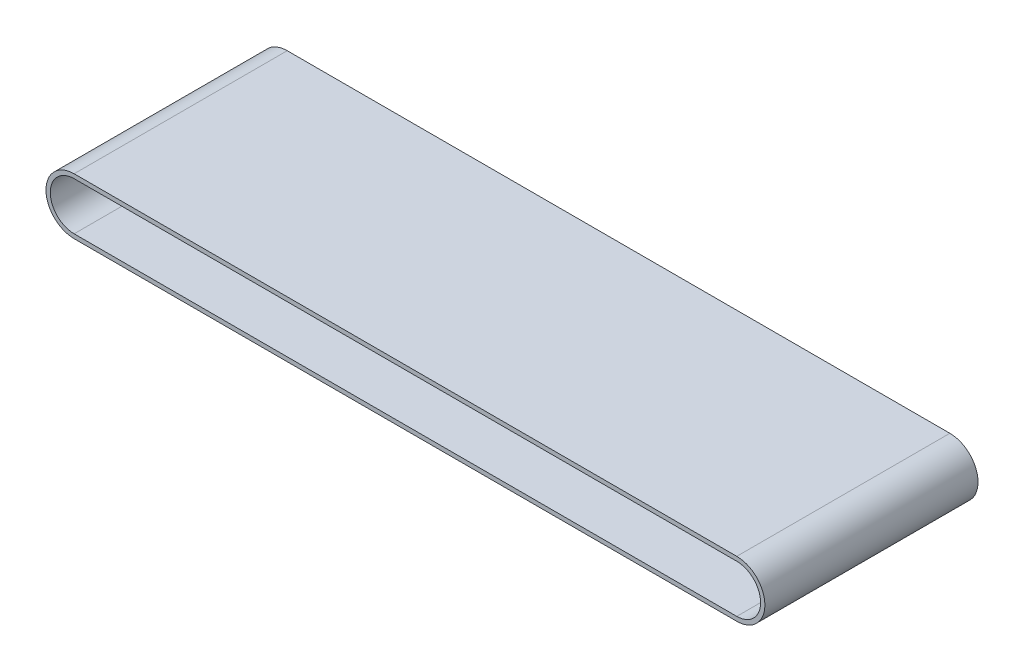
SolidWorks part; units mm, degrees
ref_plane "Front Plane" through (0, 0, 0) normal (0, 0, 1) x (1, 0, 0)
ref_plane "Top Plane" through (0, 0, 0) normal (0, 1, 0) x (1, 0, 0)
ref_plane "Right Plane" through (0, 0, 0) normal (1, 0, 0) x (0, 0, -1)
sketch "Sketch8" plane through (0, 0, 0) normal (0, 0, 1) x (1, 0, 0)
  line L0 (266.7037, 62.4154) -> (733.1037, 62.4154)
  line L4 (266.7037, 28.8154) -> (733.1037, 28.8154)
  arc A1 (266.7037, 62.4154) -> (266.7037, 28.8154) centre (266.7037, 45.6154) ccw
  arc A2 (733.1037, 62.4154) -> (733.1037, 28.8154) centre (733.1037, 45.6154) cw
  dimension "D3" = 16.8
  dimension "D2" = 16.8
  dimension "D1" = 466.4
extrude "Extrude-Thin1" add sketch "Sketch8" along normal blind 150 thin thin type one direction wall 3
